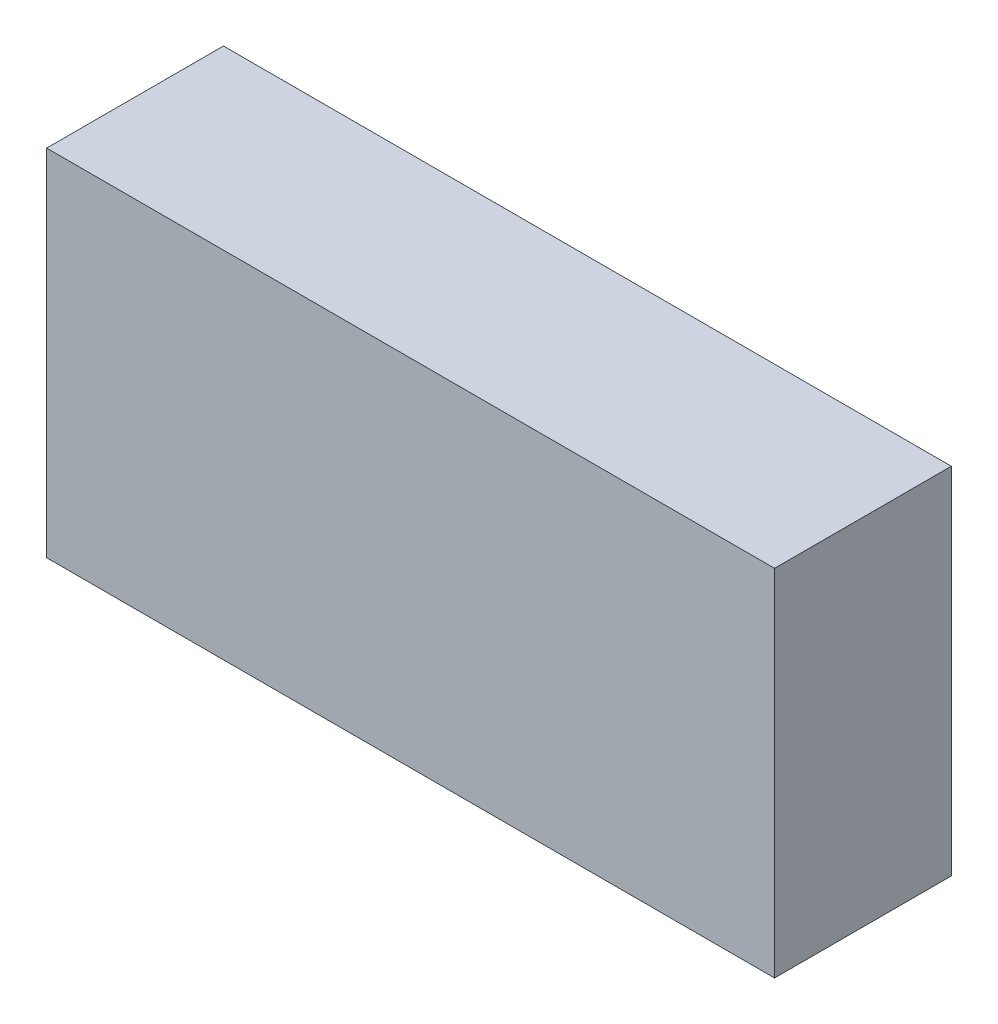
SolidWorks part; units mm, degrees
material "Pine"
ref_plane "Front Plane" through (0, 0, 0) normal (0, 0, 1) x (1, 0, 0)
ref_plane "Top Plane" through (0, 0, 0) normal (0, 1, 0) x (1, 0, 0)
ref_plane "Right Plane" through (0, 0, 0) normal (1, 0, 0) x (0, 0, -1)
sketch "Sketch1" plane through (0, 0, 0) normal (0, 1, 0) x (1, 0, 0)
  line L1 (0, 0) -> (-76.962, 0)
  line L2 (0, 0) -> (0, 18.6944)
  line L3 (0, 18.6944) -> (-76.962, 18.6944)
  line L4 (-76.962, 0) -> (-76.962, 18.6944)
  dimension "D1" = 76.962
  dimension "D2" = 18.6944
extrude "Boss-Extrude2" add sketch "Sketch1" along normal blind 37.5158 contours L3 L4 L1 L2
